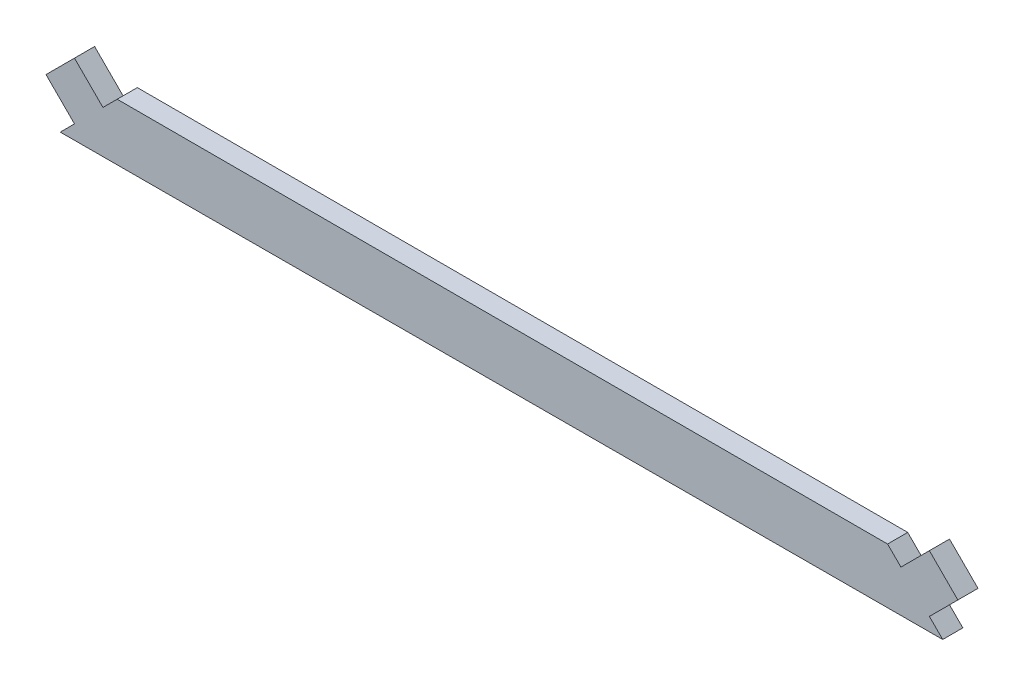
SolidWorks part; units mm, degrees
ref_plane "Front Plane" through (0, 0, 0) normal (0, 0, 1) x (1, 0, 0)
ref_plane "Top Plane" through (0, 0, 0) normal (0, 1, 0) x (1, 0, 0)
ref_plane "Right Plane" through (0, 0, 0) normal (1, 0, 0) x (0, 0, -1)
sketch "Sketch1" plane through (0, 0, 0) normal (0, 0, 1) x (1, 0, 0)
  line L0 (-139.4438, -165.8849) -> (138.8703, -165.3114)
  line L1 (0, -26.4411) -> (49.2431, -75.6842) construction
  line L2 (138.8703, -165.3114) -> (121.4833, -147.9244)
  line L3 (121.4833, -147.9244) -> (-121.4833, -147.9244)
  line L4 (-49.2431, -75.6842) -> (0, -26.4411) construction
  line L5 (-121.4833, -147.9244) -> (-139.4438, -165.8849)
  arc A0 (-204.2885, 69.85) -> (-138.8703, -165.3114) centre (0, 0) ccw construction
  dimension "D1" = 25.4
extrude "Boss-Extrude1" add sketch "Sketch1" along normal mid plane 6.35
sketch "Sketch2" plane through (0, 0, -3.175) normal (0, 0, -1) x (-1, 0, 0)
  line L0 (-130.1768, -156.6179) -> (-127.0422, -159.7525) construction
  line L1 (-138.8703, -165.3114) -> (-121.4833, -147.9244) construction
  line L2 (-125.6867, -152.1278) -> (-134.6669, -143.1475)
  line L3 (-134.6669, -143.1475) -> (-143.6472, -152.1278)
  line L4 (-143.6472, -152.1278) -> (-134.6669, -161.108)
  line L8 (-121.4833, -147.9244) -> (-125.6867, -152.1278)
  line L12 (139.4438, -165.8849) -> (121.4833, -147.9244)
  line L13 (121.4833, -147.9244) -> (-121.4833, -147.9244)
  line L14 (-121.4833, -147.9244) -> (-138.8703, -165.3114)
  line L15 (-138.8703, -165.3114) -> (139.4438, -165.8849)
  line L16 (139.4438, -165.8849) -> (121.4833, -147.9244)
  line L17 (121.4833, -147.9244) -> (-121.4833, -147.9244)
  line L18 (-134.6669, -161.108) -> (-138.8703, -165.3114)
  line L19 (-138.8703, -165.3114) -> (139.4438, -165.8849)
  dimension "D1" = 12.7
  dimension "D2" = 12.7
  dimension "D3" = 0
extrude "Boss-Extrude2" add sketch "Sketch2" against normal up to surface (6.35 mm away) up to face at (-0.1434, -156.7613, 3.175)
sketch "Sketch3" plane through (0, 0, -3.175) normal (0, 0, -1) x (-1, 0, 0)
  line L0 (130.4636, -156.9046) -> (137.1973, -150.1709) construction
  line L1 (121.4833, -147.9244) -> (139.4438, -165.8849) construction
  line L2 (125.9734, -152.4145) -> (134.9537, -143.4343)
  line L3 (134.9537, -143.4343) -> (143.9339, -152.4145)
  line L4 (143.9339, -152.4145) -> (134.9537, -161.3948)
  line L13 (139.4438, -165.8849) -> (121.4833, -147.9244)
  line L14 (121.4833, -147.9244) -> (-121.4833, -147.9244)
  line L15 (-121.4833, -147.9244) -> (-125.6867, -152.1278)
  line L16 (-125.6867, -152.1278) -> (-134.6669, -143.1475)
  line L17 (-134.6669, -143.1475) -> (-143.6472, -152.1278)
  line L18 (-143.6472, -152.1278) -> (-134.6669, -161.108)
  line L19 (-134.6669, -161.108) -> (-138.8703, -165.3114)
  line L20 (-138.8703, -165.3114) -> (139.4438, -165.8849)
  line L21 (134.9537, -161.3948) -> (125.9734, -152.4145)
  dimension "D1" = 12.7
  dimension "D2" = 12.7
  dimension "D3" = 0
extrude "Boss-Extrude4" add sketch "Sketch3" against normal blind 6.35
